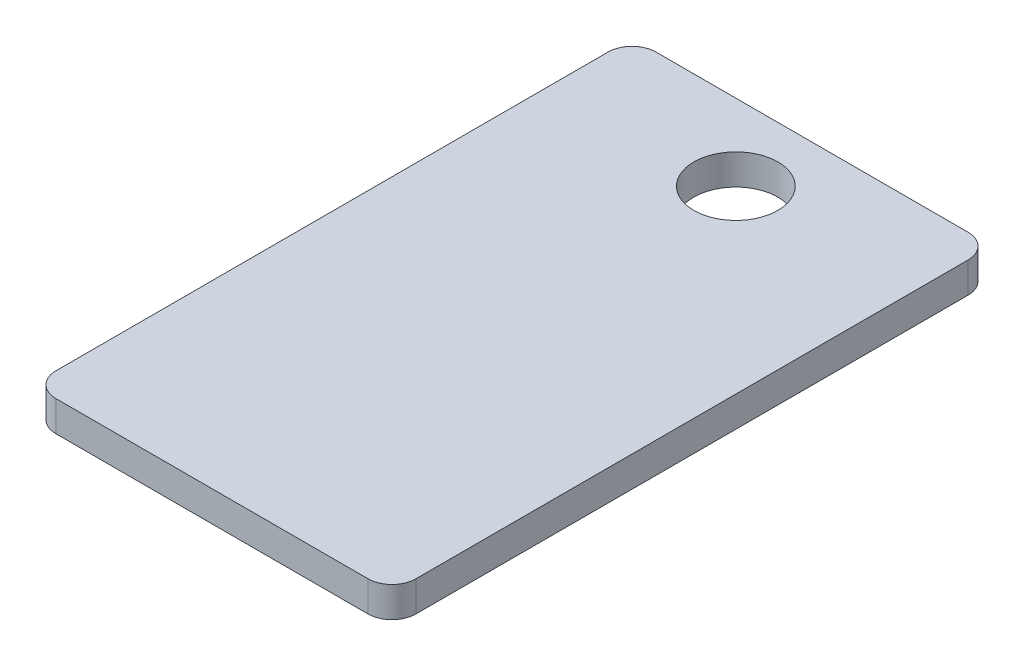
SolidWorks part; units mm, degrees
material "Copper"
ref_plane "Front Plane" through (0, 0, 0) normal (0, 0, 1) x (1, 0, 0)
ref_plane "Top Plane" through (0, 0, 0) normal (0, 1, 0) x (1, 0, 0)
ref_plane "Right Plane" through (0, 0, 0) normal (1, 0, 0) x (0, 0, -1)
sketch "Sketch1" plane through (0, 0, 0) normal (0, 1, 0) x (1, 0, 0)
  line L1 (0, 0) -> (15, 0)
  line L2 (0, 0) -> (0, -25)
  line L3 (0, -25) -> (15, -25)
  line L4 (15, 0) -> (15, -25)
  circle A0 centre (7.5, -3.175) radius 1.75
  point P8 (7.5, 0)
  dimension "D2" = 3.5
  dimension "D1" = 15
  dimension "D3" = 3.175
  dimension "D4" = 25
extrude "Boss-Extrude1" add sketch "Sketch1" along normal blind 1.27
fillet "Fillet1" radius 1 4 edges at (0, 0.635, 25) (15, 0.635, 25) (15, 0.635, 0) (0, 0.635, 0)
